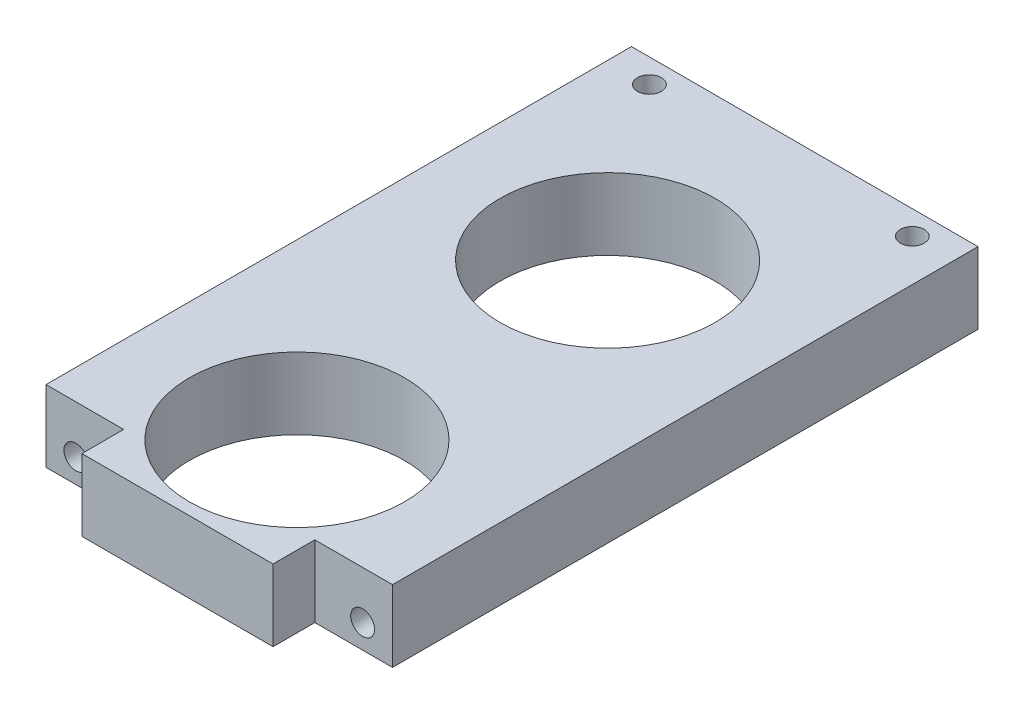
SolidWorks part; units mm, degrees
material "6061 合金"
ref_plane "前视基准面" through (0, 0, 0) normal (0, 0, 1) x (1, 0, 0)
ref_plane "上视基准面" through (0, 0, 0) normal (0, 1, 0) x (1, 0, 0)
ref_plane "右视基准面" through (0, 0, 0) normal (1, 0, 0) x (0, 0, -1)
sketch "草图1" plane through (0, 0, 0) normal (0, 1, 0) x (1, 0, 0)
  line L1 (-14.5, -26.25) -> (14.5, -26.25)
  line L2 (-14.5, -26.25) -> (-14.5, 26.25)
  line L3 (-14.5, 26.25) -> (14.5, 26.25)
  line L4 (14.5, -26.25) -> (14.5, 26.25)
  line L5 (-14.5, -26.25) -> (14.5, 26.25) construction
  line L6 (-14.5, 26.25) -> (14.5, -26.25) construction
  circle A0 centre (0, -16.25) radius 9
  circle A1 centre (0, -4.25) radius 2.25 construction
  circle A2 centre (0, 9.75) radius 9
  circle A3 centre (0, 21.75) radius 2.25 construction
  point P0 (0, 0)
  dimension "D12" = 4.5
  dimension "D13" = 4.5
  dimension "D14" = 18
  dimension "D1" = 29
  dimension "D2" = 16.5
  dimension "D6" = 14.5
  dimension "D7" = 12
  dimension "D8" = 10
  dimension "D9" = 26
  dimension "D10" = 12
extrude "凸台-拉伸1" add sketch "草图1" along normal blind 6
sketch "草图2" plane through (0, 6, 0) normal (0, 1, 0) x (1, 0, 0)
  line L0 (-14.5, 26.25) -> (-14.5, -26.25) construction
  line L1 (-14.5, -22.75) -> (-8, -22.75)
  line L2 (-14.5, -22.75) -> (-14.5, -26.25)
  line L3 (-14.5, -26.25) -> (-8, -26.25)
  line L4 (-8, -22.75) -> (-8, -26.25)
  line L5 (-14.5, -26.25) -> (14.5, -26.25) construction
  line L6 (0, -26.25) -> (0, -17.1796) construction
  line L11 (14.5, -26.25) -> (8, -26.25)
  line L12 (8, -22.75) -> (8, -26.25)
  line L13 (14.5, -22.75) -> (8, -22.75)
  line L14 (14.5, -22.75) -> (14.5, -26.25)
  dimension "D1" = 3.5
  dimension "D2" = 16
extrude "切除-拉伸1" cut sketch "草图2" against normal blind 10
sketch "草图3" plane through (0, 0, 22.75) normal (0, 0, 1) x (1, 0, 0)
  line L0 (-8, 6) -> (-14.5, 6) construction
  line L1 (-8, 6) -> (-8, 0) construction
  line L2 (8, 0) -> (8, 6) construction
  line L3 (14.5, 6) -> (8, 6) construction
  circle A0 centre (-12, 2) radius 1
  circle A1 centre (12, 2) radius 1
  dimension "D2" = 2
  dimension "D6" = 2
  dimension "D1" = 4
  dimension "D3" = 4
  dimension "D4" = 4
  dimension "D5" = 4
extrude "切除-拉伸4" cut sketch "草图3" against normal blind 8
cosmetic thread "装饰螺纹线1" parameters "D2"=3
cosmetic thread "装饰螺纹线3" parameters "D2"=4
sketch "草图4" plane through (0, 6, 0) normal (0, 1, 0) x (1, 0, 0)
  line L0 (14.5, 26.25) -> (-14.5, 26.25) construction
  line L1 (0, 26.25) -> (0, 20.2081) construction
  circle A0 centre (-11, 24.25) radius 1
  circle A1 centre (11, 24.25) radius 1
  point P9 (0, 0)
  dimension "D1" = 2
  dimension "D2" = 22
  dimension "D3" = 2
  dimension "D4" = 11
extrude "切除-拉伸5" cut sketch "草图4" against normal blind 10
cosmetic thread "装饰螺纹线4" parameters "D2"=3
cosmetic thread "装饰螺纹线5" parameters "D2"=3
